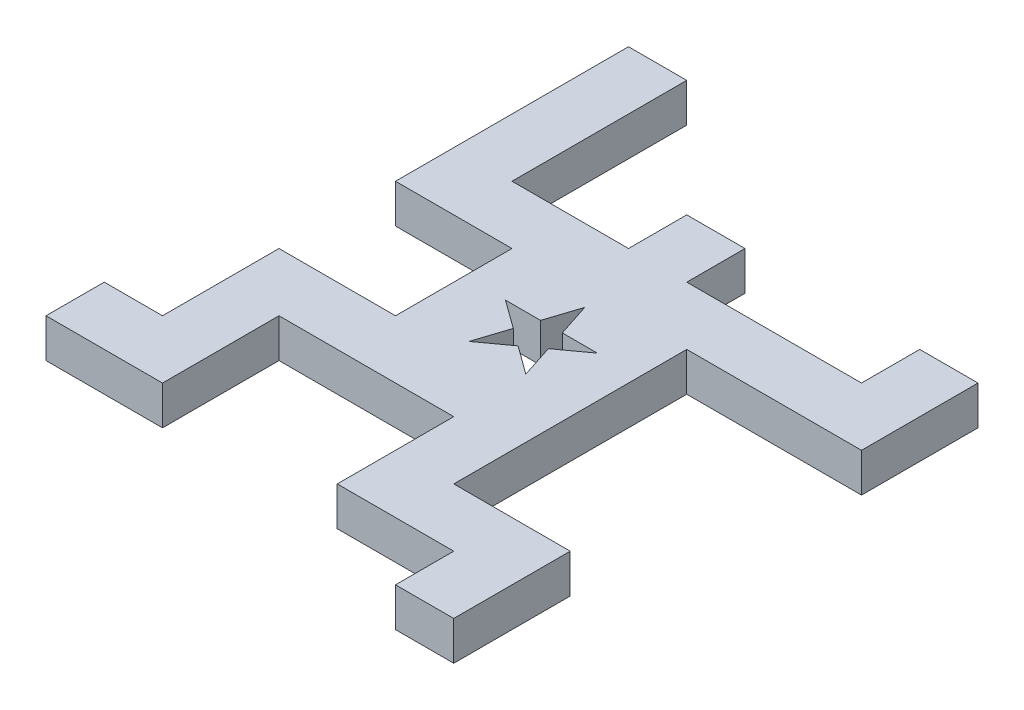
SolidWorks part; units mm, degrees
ref_plane "Front Plane" through (0, 0, 0) normal (0, 0, 1) x (1, 0, 0)
ref_plane "Top Plane" through (0, 0, 0) normal (0, 1, 0) x (1, 0, 0)
ref_plane "Right Plane" through (0, 0, 0) normal (1, 0, 0) x (0, 0, -1)
sketch "Sketch1" plane through (0, 0, 0) normal (0, 1, 0) x (1, 0, 0)
  line L0 (11.25, 15) -> (26.25, 15)
  line L1 (-11.25, 15) -> (11.25, 15)
  line L2 (-11.25, 15) -> (-11.25, -15)
  line L3 (-11.25, -15) -> (11.25, -15)
  line L4 (11.25, 15) -> (11.25, -15)
  line L5 (-11.25, 15) -> (11.25, -15) construction
  line L6 (-11.25, -15) -> (11.25, 15) construction
  line L7 (-3.75, 15) -> (3.75, 15)
  line L8 (-3.75, 15) -> (-3.75, 22.5)
  line L9 (-3.75, 22.5) -> (3.75, 22.5)
  line L10 (3.75, 15) -> (3.75, 22.5)
  line L11 (26.25, 15) -> (26.25, 22.5)
  line L12 (26.25, 22.5) -> (33.75, 22.5)
  line L13 (33.75, 22.5) -> (33.75, 7.5)
  line L14 (33.75, 7.5) -> (11.25, 7.5)
  line L15 (-11.25, 15) -> (-18.75, 15)
  line L16 (-18.75, 15) -> (-18.75, 37.5)
  line L17 (-18.75, 37.5) -> (-26.25, 37.5)
  line L18 (-26.25, 37.5) -> (-26.25, 7.5)
  line L19 (-26.25, 7.5) -> (-11.25, 7.5)
  line L20 (11.25, -15) -> (11.25, -22.5)
  line L21 (11.25, -22.5) -> (26.25, -22.5)
  line L22 (26.25, -22.5) -> (26.25, -37.5)
  line L23 (26.25, -37.5) -> (18.75, -37.5)
  line L24 (18.75, -37.5) -> (18.75, -30)
  line L25 (18.75, -30) -> (3.75, -30)
  line L26 (3.75, -30) -> (3.75, -15)
  line L27 (-11.25, -15) -> (-18.75, -15)
  line L28 (-18.75, -15) -> (-18.75, -30)
  line L29 (-18.75, -30) -> (-33.75, -30)
  line L30 (-33.75, -30) -> (-33.75, -22.5)
  line L31 (-33.75, -22.5) -> (-26.25, -22.5)
  line L32 (-26.25, -22.5) -> (-26.25, -7.5)
  line L33 (-26.25, -7.5) -> (-11.25, -7.5)
  point P0 (0, 0)
  dimension "D1" = 30
  dimension "D2" = 22.5
  dimension "D3" = 7.5
  dimension "D4" = 7.5
  dimension "D5" = 7.5
  dimension "D6" = 7.5
  dimension "D7" = 15
  dimension "D8" = 22.5
  dimension "D9" = 15
  dimension "D10" = 30
  dimension "D11" = 7.5
  dimension "D12" = 7.5
  dimension "D13" = 15
  dimension "D14" = 15
  dimension "D15" = 7.5
  dimension "D16" = 15
  dimension "D17" = 15
  dimension "D18" = 7.5
  dimension "D19" = 7.5
  dimension "D20" = 15
  dimension "D21" = 7.5
  dimension "D22" = 7.5
  dimension "D23" = 7.5
  dimension "D24" = 7.5
extrude "Boss-Extrude1" add sketch "Sketch1" along normal blind 5 contours L18 L19 L2 L15 L16 L17 | L4 L1 L2 L3 | L1 L10 L9 L8 | L14 L13 L12 L11 L0 L4 | L26 L25 L24 L23 L22 L21 L20 L3 | L33 L32 L31 L30 L29 L28 L27 L2
sketch "Sketch2" plane through (0, 5, 0) normal (0, 1, 0) x (1, 0, 0)
  line L0 (-11.25, 7.5) -> (11.25, 7.5) construction
  line L1 (-11.25, -7.5) -> (11.25, -7.5) construction
  line L2 (11.25, 7.5) -> (11.25, -22.5) construction
  line L3 (0, 5.625) -> (0, -7.5) construction
  line L4 (0, 5.625) -> (-1.3962, 1.3279)
  line L5 (-1.3962, 1.3279) -> (-5.9145, 1.3279)
  line L6 (-5.9145, 1.3279) -> (-2.2591, -1.3279)
  line L7 (-2.2591, -1.3279) -> (-3.6553, -5.625)
  line L8 (-3.6553, -5.625) -> (0, -2.9692)
  line L9 (3.6553, -5.625) -> (0, -2.9692)
  line L10 (2.2591, -1.3279) -> (3.6553, -5.625)
  line L11 (5.9145, 1.3279) -> (2.2591, -1.3279)
  line L12 (1.3962, 1.3279) -> (5.9145, 1.3279)
  line L13 (0, 5.625) -> (1.3962, 1.3279)
  dimension "D2" = 252
  dimension "D3" = 36
  dimension "D4" = 252
  dimension "D5" = 36
  dimension "D1" = 1.875
  dimension "D6" = 1.875
extrude "Cut-Extrude1" cut sketch "Sketch2" against normal through all
equation "\"Square Width\" = 7.5mm"
equation "\"Square Height\"= 7.5mm"
equation "\"Tolerance\"= 1mm"
equation "\"Block Height\" = 5mm"
equation "\"Base Height\"= 10mm"
equation "\"D1@Sketch1\"=\"Square Height\"*4"
equation "\"D2@Sketch1\"=\"Square Width\"*3"
equation "\"D3@Sketch1\"=\"Square Width\""
equation "\"D4@Sketch1\"=\"Square Height\""
equation "\"D5@Sketch1\"=\"Square Width\""
equation "\"D6@Sketch1\"=\"Square Width\""
equation "\"D7@Sketch1\"=\"Square Height\"*2"
equation "\"D8@Sketch1\"=\"Square Width\"*3"
equation "\"D9@Sketch1\"=\"Square Width\"*2"
equation "\"D10@Sketch1\"=\"Square Height\"*4"
equation "\"D11@Sketch1\"=\"Square Width\""
equation "\"D12@Sketch1\"=\"Square Height\""
equation "\"D13@Sketch1\"=\"Square Height\"*2"
equation "\"D14@Sketch1\"=\"Square Width\"*2"
equation "\"D15@Sketch1\"=\"Square Height\""
equation "\"D16@Sketch1\"=\"Square Height\"*2"
equation "\"D17@Sketch1\"=\"Square Width\"*2"
equation "\"D18@Sketch1\"=\"Square Width\""
equation "\"D19@Sketch1\"=\"Square Width\""
equation "\"D20@Sketch1\"=\"Square Height\"*2"
equation "\"D21@Sketch1\"=\"Square Height\""
equation "\"D22@Sketch1\"=\"Square Width\""
equation "\"D23@Sketch1\"=\"Square Width\""
equation "\"D24@Sketch1\"=\"Square Height\""
equation "\"D1@Boss-Extrude1\"=\"Block Height\""
equation "\"D1@Sketch2\"=\"Square Height\"/4"
equation "\"D6@Sketch2\"=\"Square Height\"/4"
